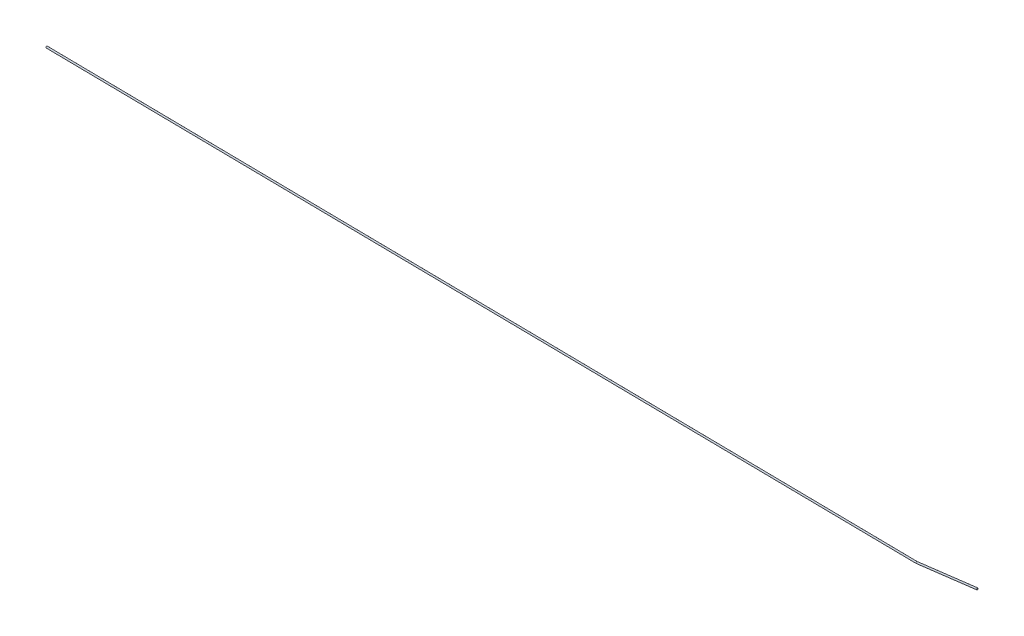
SolidWorks part; units mm, degrees
material "Nickel"
ref_plane "Front Plane" through (0, 0, 0) normal (0, 0, 1) x (1, 0, 0)
ref_plane "Top Plane" through (0, 0, 0) normal (0, 1, 0) x (1, 0, 0)
ref_plane "Right Plane" through (0, 0, 0) normal (1, 0, 0) x (0, 0, -1)
sketch3d "3DSketch1"
  line L0 (-340.7632, -15.7669, 10.2876) -> (323.744, -25.1067, 9.6847)
  line L1 (323.744, -25.1067, 9.6847) -> (365.0703, -24.4409, 4.6548)
sweep "Sweep1" add path "3DSketch1" circular profile diameter 1.2 parameters "D3"=1.2
